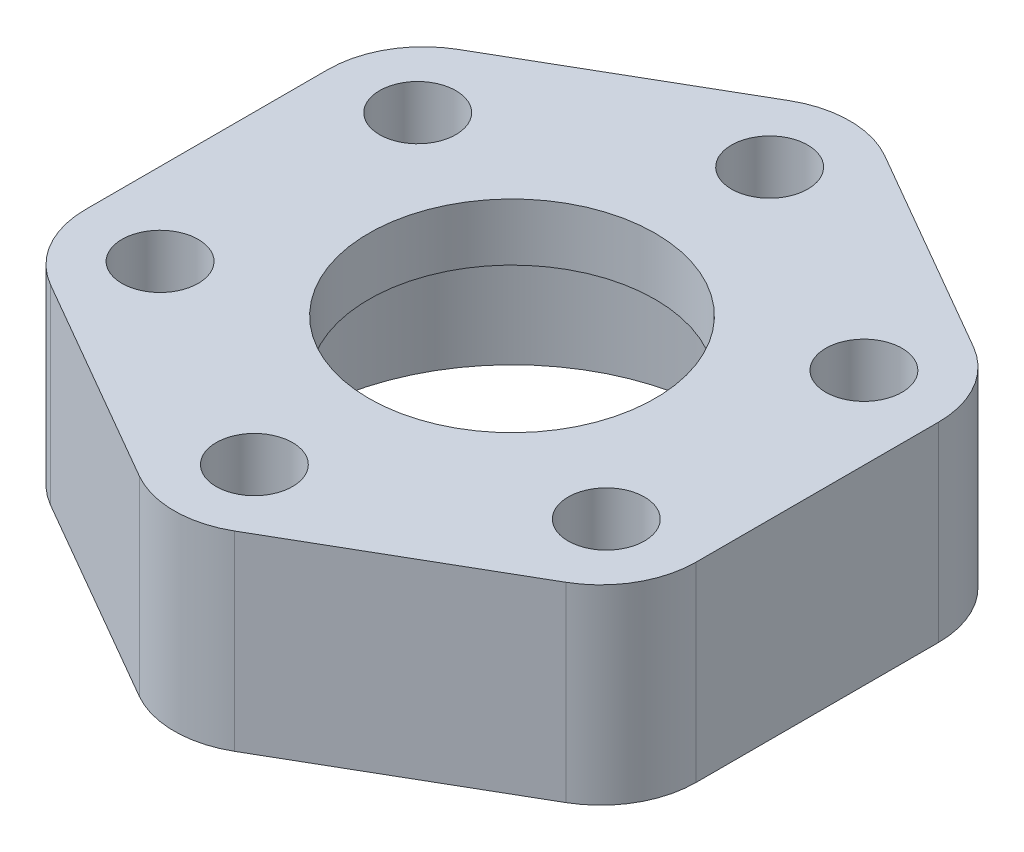
SolidWorks part; units mm, degrees
ref_plane "Front Plane" through (0, 0, 0) normal (0, 0, 1) x (1, 0, 0)
ref_plane "Top Plane" through (0, 0, 0) normal (0, 1, 0) x (1, 0, 0)
ref_plane "Right Plane" through (0, 0, 0) normal (1, 0, 0) x (0, 0, -1)
sketch "Sketch1" plane through (0, 0, 0) normal (0, 1, 0) x (1, 0, 0)
  line L1 (-2.5, 17.0318) -> (-13.5, 10.681)
  line L2 (-16, 6.3509) -> (-16, -6.3509)
  line L3 (-13.5, -10.681) -> (-2.5, -17.0318)
  line L4 (2.5, -17.0318) -> (13.5, -10.681)
  line L5 (16, -6.3509) -> (16, 6.3509)
  line L6 (13.5, 10.681) -> (2.5, 17.0318)
  circle A0 centre (0, 0) radius 11
  circle A1 centre (0, 0) radius 13.5 construction
  circle A2 centre (0, 0) radius 16 construction
  circle A3 centre (0, 13.5) radius 2
  circle A4 centre (11.6913, 6.75) radius 2
  circle A5 centre (11.6913, -6.75) radius 2
  circle A6 centre (0, -13.5) radius 2
  circle A7 centre (-11.6913, -6.75) radius 2
  circle A8 centre (-11.6913, 6.75) radius 2
  circle A9 centre (0, 0) radius 16 construction
  arc A10 (-13.5, 10.681) -> (-16, 6.3509) centre (-11, 6.3509) ccw
  arc A11 (-16, -6.3509) -> (-13.5, -10.681) centre (-11, -6.3509) ccw
  arc A12 (-2.5, -17.0318) -> (2.5, -17.0318) centre (0, -12.7017) ccw
  arc A13 (13.5, -10.681) -> (16, -6.3509) centre (11, -6.3509) ccw
  arc A14 (16, 6.3509) -> (13.5, 10.681) centre (11, 6.3509) ccw
  arc A15 (-2.5, 17.0318) -> (2.5, 17.0318) centre (0, 12.7017) cw
  point P19 (0, 0)
  dimension "D1" = 22
  dimension "D2" = 27
  dimension "D3" = 32
  dimension "D4" = 4
  dimension "D6" = 5
  dimension "D5" = 6
extrude "Boss-Extrude1" add sketch "Sketch1" along normal blind 10
sketch "Sketch2" plane through (0, 10, 0) normal (0, 1, 0) x (1, 0, 0)
  circle A0 centre (0, 0) radius 11
  circle A1 centre (0, 0) radius 7.5
  dimension "D1" = 15
extrude "Boss-Extrude2" add sketch "Sketch2" against normal blind 3
